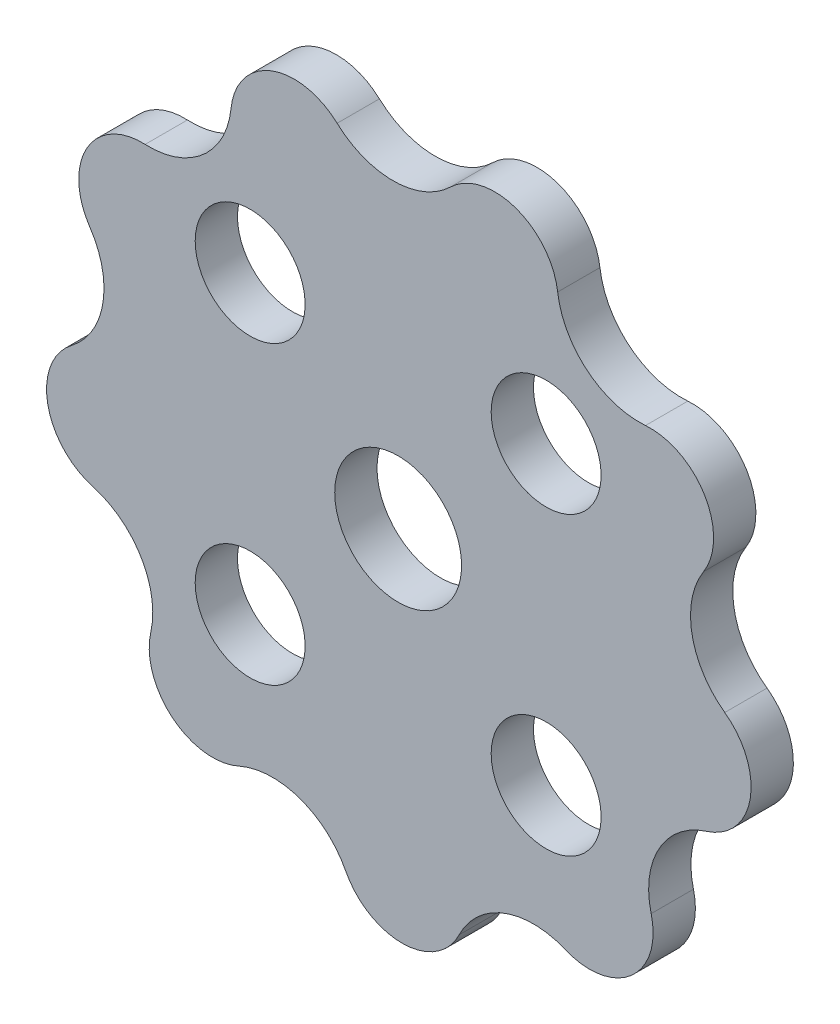
SolidWorks part; units mm, degrees
ref_plane "Front Plane" through (0, 0, 0) normal (0, 0, 1) x (1, 0, 0)
ref_plane "Top Plane" through (0, 0, 0) normal (0, 1, 0) x (1, 0, 0)
ref_plane "Right Plane" through (0, 0, 0) normal (1, 0, 0) x (0, 0, -1)
sketch "Sketch1" plane through (0, 0, 0) normal (0, 0, 1) x (1, 0, 0)
  line L0 (12.3881, 76.2502) -> (0, 0) construction
  line L1 (0, 0) -> (22.8492, 65.5) construction
  line L2 (0, 0) -> (58.5026, 50.4481) construction
  circle A0 centre (0, 0) radius 77.25 construction
  arc A1 (12.3881, 76.2502) -> (37.7269, 67.411) centre (22.8492, 65.5) cw
  arc A2 (37.7269, 67.411) -> (58.5026, 50.4481) centre (57.068, 69.8953) ccw
  arc A3 (58.5026, 50.4481) -> (72.2315, 27.3894) centre (59.6061, 35.4888) cw
  arc A4 (72.2315, 27.3894) -> (77.243, 1.0408) centre (88.6445, 16.8603) ccw
  arc A5 (77.243, 1.0408) -> (72.9381, -25.448) centre (68.4726, -11.1281) cw
  arc A6 (72.9381, -25.448) -> (59.8406, -48.8536) centre (78.7432, -44.0639) ccw
  arc A7 (59.8406, -48.8536) -> (39.5162, -66.378) centre (45.3001, -52.5379) cw
  arc A8 (39.5162, -66.378) -> (14.4381, -75.8888) centre (31.9971, -84.37) ccw
  arc A9 (14.4381, -75.8888) -> (-12.3958, -76.249) centre (0.9311, -69.3647) cw
  arc A10 (-12.3958, -76.249) -> (-37.7202, -67.4148) centre (-29.7208, -85.1985) ccw
  arc A11 (-37.7202, -67.4148) -> (-58.5076, -50.4422) centre (-43.8735, -53.735) cw
  arc A12 (-58.5076, -50.4422) -> (-72.2287, -27.3967) centre (-77.532, -46.1617) ccw
  arc A13 (-72.2287, -27.3967) -> (-77.2431, -1.033) centre (-68.1492, -12.9621) cw
  arc A14 (-77.2431, -1.033) -> (-72.9406, 25.4407) centre (-89.0651, 14.4747) ccw
  arc A15 (-72.9406, 25.4407) -> (-59.8357, 48.8596) centre (-60.5372, 33.876) cw
  arc A16 (-59.8357, 48.8596) -> (-39.5228, 66.374) centre (-58.9236, 68.3382) ccw
  arc A17 (-39.5228, 66.374) -> (-14.4304, 75.8902) centre (-24.5991, 64.8631) cw
  arc A18 (-14.4304, 75.8902) -> (12.3881, 76.2502) centre (-1.2112, 90.2255) ccw
  point P51 (0, 0)
  dimension "D1" = 154.5
  dimension "D3" = 19.5
  dimension "D4" = 15
  dimension "D2" = 65.5
  dimension "D5" = 40
  dimension "D6" = 9
extrude "Boss-Extrude1" add sketch "Sketch1" along normal blind 10 contours A18 A17 A16 A15 A14 A13 A12 A11 A10 A9 A8 A7 A6 A5 A4 A3 A2 A1
sketch "Sketch3" plane through (0, 0, 0) normal (0, 0, -1) x (-1, 0, 0)
  line L0 (-34.0213, 0) -> (0, 0) construction
  line L1 (0, 0) -> (0, 44.925) construction
  line L2 (-35, 35) -> (0, 0) construction
  circle A0 centre (-35, 35) radius 13
  circle A1 centre (35, 35) radius 13
  circle A2 centre (35, -35) radius 13
  circle A3 centre (-35, -35) radius 13
  circle A4 centre (0, 0) radius 15
  point P15 (0, 0)
  dimension "D2" = 26
  dimension "D5" = 30
  dimension "D1" = 45
  dimension "D3" = 35
  dimension "D4" = 4
extrude "Cut-Extrude1" cut sketch "Sketch3" against normal through all
